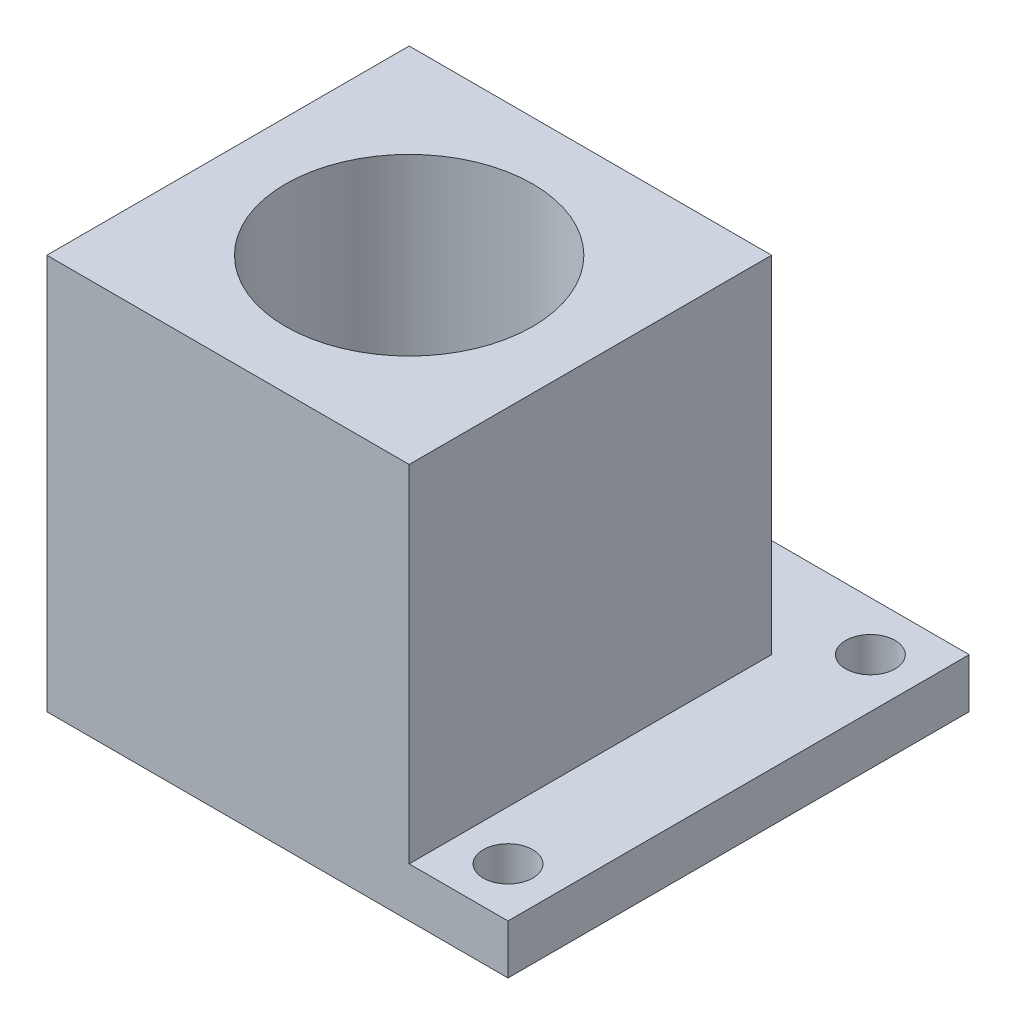
SolidWorks part; units mm, degrees
ref_plane "Front Plane" through (0, 0, 0) normal (0, 0, 1) x (1, 0, 0)
ref_plane "Top Plane" through (0, 0, 0) normal (0, 1, 0) x (1, 0, 0)
ref_plane "Right Plane" through (0, 0, 0) normal (1, 0, 0) x (0, 0, -1)
sketch "Sketch1" plane through (0, 0, 0) normal (0, 1, 0) x (1, 0, 0)
  line L1 (0, 0) -> (22, 0)
  line L2 (0, 0) -> (0, 22)
  line L3 (0, 22) -> (22, 22)
  line L4 (22, 0) -> (22, 22)
  circle A0 centre (11, 11) radius 7.5
  dimension "D1" = 15
  dimension "D2" = 11
  dimension "D3" = 11
  dimension "D4" = 22
  dimension "D5" = 22
extrude "Boss-Extrude1" add sketch "Sketch1" along normal blind 24
sketch "Sketch2" plane through (0, 0, 0) normal (0, -1, 0) x (1, 0, 0)
  line L0 (0, -22) -> (22, -22)
  line L1 (22, -22) -> (22, 0)
  line L2 (22, 0) -> (28, 0)
  line L3 (28, 0) -> (28, -28)
  line L4 (28, -28) -> (0, -28)
  line L5 (0, -28) -> (0, -22)
  line L6 (0, -22) -> (-0.1475, -21.7249)
  circle A0 centre (25, -25) radius 1.5
  circle A1 centre (25, -3) radius 1.5
  circle A2 centre (3, -25) radius 1.5
  line M6 (0, -22) -> (22, -22)
  line M7 (22, -22) -> (22, 0)
  dimension "D1" = 3
  dimension "D2" = 3
  dimension "D3" = 3
  dimension "D4" = 6
  dimension "D5" = 6
  dimension "D6" = 3
  dimension "D7" = 3
  dimension "D8" = 3
  dimension "D9" = 3
extrude "Boss-Extrude2" add sketch "Sketch2" against normal blind 3 contours L5 L4 L3 L2 A0 M7 M6
